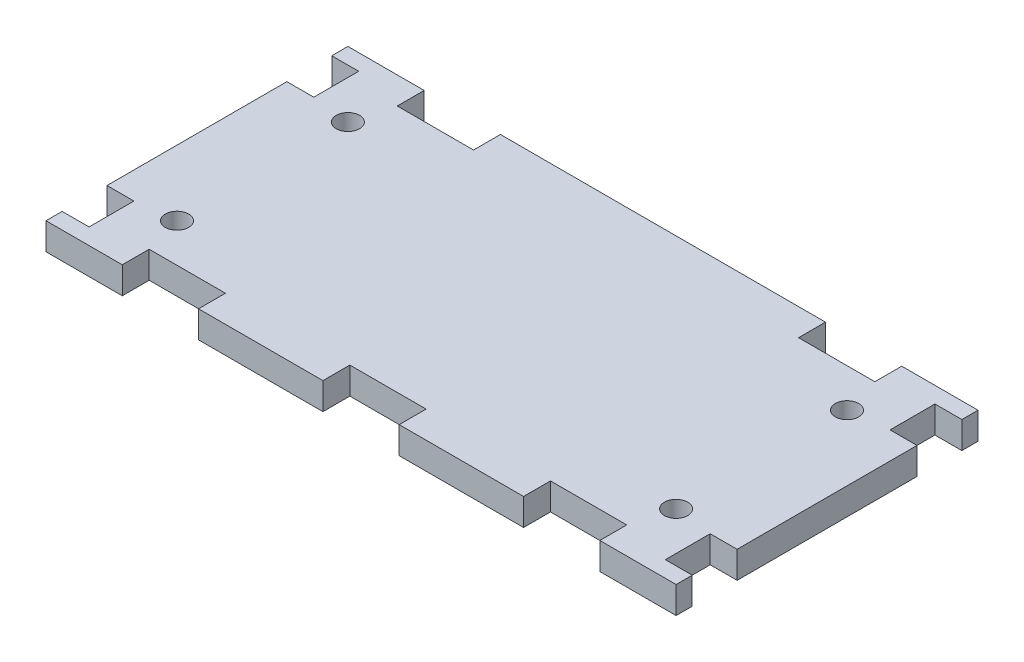
SolidWorks part; units mm, degrees
material "Balsa"
ref_plane "Alzado" through (0, 0, 0) normal (0, 0, 1) x (1, 0, 0)
ref_plane "Planta" through (0, 0, 0) normal (0, 1, 0) x (1, 0, 0)
ref_plane "Vista lateral" through (0, 0, 0) normal (1, 0, 0) x (0, 0, -1)
sketch "Croquis1" plane through (0, 0, 0) normal (0, 1, 0) x (1, 0, 0)
  line L0 (17, 33.65) -> (30.865, 33.65)
  line L1 (0, 0) -> (8.5, 0)
  line L2 (0, 0) -> (0, 1.8)
  line L3 (0, 33.65) -> (8.5, 33.65)
  line L4 (70.23, 0) -> (70.23, 1.8)
  line L6 (8.5, 33.65) -> (8.5, 30.65)
  line L7 (8.5, 30.65) -> (17, 30.65)
  line L8 (17, 33.65) -> (17, 30.65)
  line L14 (53.23, 33.65) -> (53.23, 30.65)
  line L15 (53.23, 30.65) -> (61.73, 30.65)
  line L16 (61.73, 33.65) -> (61.73, 30.65)
  line L18 (8.5, 0) -> (8.5, 3)
  line L19 (8.5, 3) -> (17, 3)
  line L20 (17, 0) -> (17, 3)
  line L22 (30.865, 0) -> (30.865, 3)
  line L23 (30.865, 3) -> (39.365, 3)
  line L24 (39.365, 0) -> (39.365, 3)
  line L26 (53.23, 0) -> (53.23, 3)
  line L27 (53.23, 3) -> (61.73, 3)
  line L28 (61.73, 0) -> (61.73, 3)
  line L29 (39.365, 33.65) -> (53.23, 33.65)
  line L30 (61.73, 33.65) -> (70.23, 33.65)
  line L31 (17, 0) -> (30.865, 0)
  line L32 (39.365, 0) -> (53.23, 0)
  line L33 (61.73, 0) -> (70.23, 0)
  line L34 (0, 31.85) -> (0, 33.65)
  line L35 (0, 31.85) -> (3, 31.85)
  line L37 (0, 26.85) -> (3, 26.85)
  line L38 (3, 31.85) -> (3, 26.85)
  line L39 (0, 1.8) -> (3, 1.8)
  line L41 (0, 6.8) -> (3, 6.8)
  line L42 (3, 1.8) -> (3, 6.8)
  line L43 (70.23, 31.85) -> (67.23, 31.85)
  line L45 (70.23, 26.85) -> (67.23, 26.85)
  line L46 (67.23, 31.85) -> (67.23, 26.85)
  line L47 (70.23, 6.8) -> (67.23, 6.8)
  line L49 (70.23, 1.8) -> (67.23, 1.8)
  line L50 (67.23, 6.8) -> (67.23, 1.8)
  line L51 (0, 6.8) -> (0, 26.85)
  line L52 (70.23, 31.85) -> (70.23, 33.65)
  line L53 (70.23, 6.8) -> (70.23, 26.85)
  line L54 (30.865, 33.65) -> (39.365, 33.65)
  circle A0 centre (7.3, 26.35) radius 1.3
  circle A1 centre (7.3, 7.3) radius 1.3
  circle A2 centre (62.93, 26.35) radius 1.3
  circle A3 centre (62.93, 7.3) radius 1.3
  dimension "D3" = 2.6
  dimension "D1" = 70.23
  dimension "D2" = 33.65
  dimension "D4" = 7.3
  dimension "D5" = 7.3
  dimension "D6" = 7.3
  dimension "D7" = 7.3
  dimension "D8" = 8.5
  dimension "D9" = 3
  dimension "D10" = 8.5
  dimension "D11" = 8.5
  dimension "D12" = 8.5
  dimension "D13" = 8.5
  dimension "D14" = 3
  dimension "D15" = 3
  dimension "D16" = 5
  dimension "D17" = 5
  dimension "D18" = 5
  dimension "D19" = 3
  dimension "D20" = 5
  dimension "D21" = 3
  dimension "D22" = 1.8
  dimension "D23" = 1.8
  dimension "D24" = 8.5
  dimension "D25" = 8.5
extrude "Saliente-Extruir1" add sketch "Croquis1" along normal blind 3
